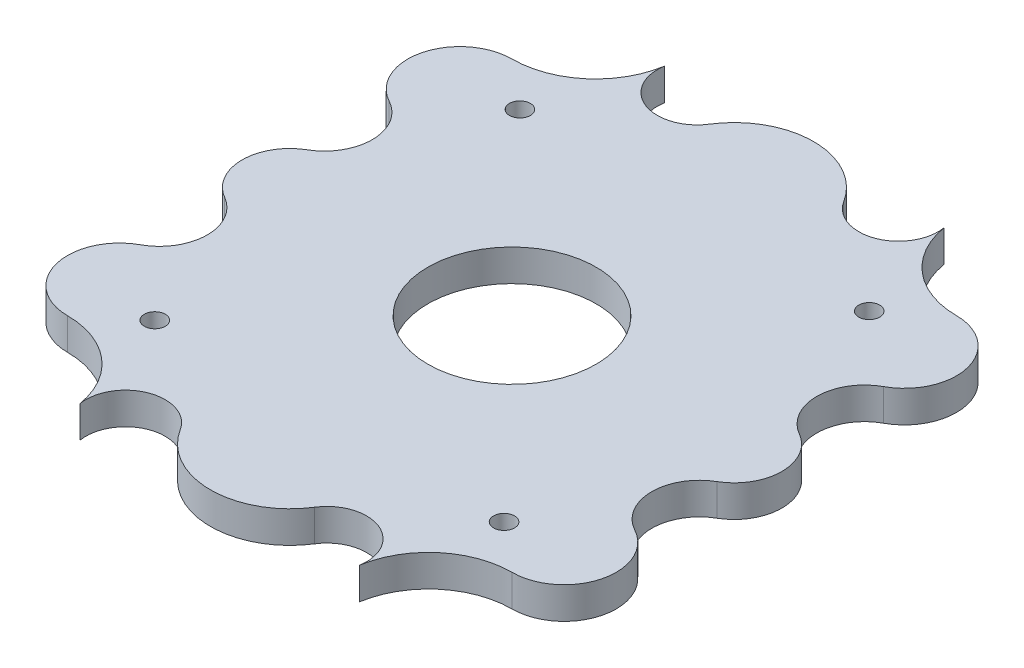
SolidWorks part; units mm, degrees
ref_plane "Alzado" through (0, 0, 0) normal (0, 0, 1) x (1, 0, 0)
ref_plane "Planta" through (0, 0, 0) normal (0, 1, 0) x (1, 0, 0)
ref_plane "Vista lateral" through (0, 0, 0) normal (1, 0, 0) x (0, 0, -1)
sketch "Croquis1" plane through (0, 0, 0) normal (0, 1, 0) x (1, 0, 0)
  line L0 (0, 138.5041) -> (0, -177.2184) construction
  line L2 (-70, -70) -> (-70, 70)
  line L4 (70, -70) -> (70, 70)
  line L5 (-70, -70) -> (70, 70) construction
  line L6 (-70, 70) -> (70, -70) construction
  line L7 (-103.4324, 0) -> (144.2109, 0) construction
  arc A1 (-21.1476, -83.3333) -> (21.1476, -83.3333) centre (0, -70) ccw
  arc A5 (-21.1476, -83.3333) -> (-44.0559, -92.0276) centre (-31.7214, -90) ccw
  arc A6 (-44.0559, -92.0276) -> (-70, -70) centre (-70, -96.2923) ccw
  arc A7 (21.1476, -83.3333) -> (44.0559, -92.0276) centre (31.7214, -90) cw
  arc A8 (44.0559, -92.0276) -> (70, -70) centre (70, -96.2923) cw
  arc A9 (44.0559, 92.0276) -> (70, 70) centre (70, 96.2923) ccw
  arc A10 (21.1476, 83.3333) -> (44.0559, 92.0276) centre (31.7214, 90) ccw
  arc A11 (-21.1476, 83.3333) -> (21.1476, 83.3333) centre (0, 70) cw
  arc A12 (-21.1476, 83.3333) -> (-44.0559, 92.0276) centre (-31.7214, 90) cw
  arc A13 (-44.0559, 92.0276) -> (-70, 70) centre (-70, 96.2923) cw
  point P0 (0, 0)
  point P14 (-25, -70)
  point P16 (-70, -70)
  dimension "D4" = 50
  dimension "D6" = 25
  dimension "D1" = 140
  dimension "D2" = 140
extrude "Saliente-Extruir1" add sketch "Croquis1" along normal blind 10
sketch "Croquis2" plane through (0, 10, 0) normal (0, 1, 0) x (1, 0, 0)
  line L0 (70, -70) -> (70, 70) construction
  line L1 (70, 70) -> (70, -70)
  line L2 (0, 152.4123) -> (0, -148.5895) construction
  line L3 (-96.3545, 0) -> (168.0513, 0) construction
  line L4 (-70, 70) -> (-70, -70)
  arc A0 (77.5, -12.9904) -> (77.5, 12.9904) centre (70, 0) ccw
  arc A1 (77.838, 39.1605) -> (77.5, 12.9904) centre (85, 25.9808) ccw
  arc A2 (77.838, 39.1605) -> (70, 70) centre (70, 53.5842) ccw
  arc A3 (77.838, -39.1605) -> (77.5, -12.9904) centre (85, -25.9808) cw
  arc A4 (77.838, -39.1605) -> (70, -70) centre (70, -53.5842) cw
  arc A5 (-77.838, -39.1605) -> (-70, -70) centre (-70, -53.5842) ccw
  arc A6 (-77.838, -39.1605) -> (-77.5, -12.9904) centre (-85, -25.9808) ccw
  arc A7 (-77.5, -12.9904) -> (-77.5, 12.9904) centre (-70, 0) cw
  arc A8 (-77.838, 39.1605) -> (-77.5, 12.9904) centre (-85, 25.9808) cw
  arc A9 (-77.838, 39.1605) -> (-70, 70) centre (-70, 53.5842) cw
  line M11 (-70, 70) -> (-70, -70)
  line M17 (70, -70) -> (70, 70)
  dimension "D1" = 30
  dimension "D2" = 30
extrude "Saliente-Extruir2" add sketch "Croquis2" against normal blind 10 contours A9 A8 M11 | A1 A2 L1 | L1 A3 A0 A1 | L4 A8 A7 A6 | A6 A5 L4 | A4 A3 M17
sketch "Croquis3" plane through (0, 10, 0) normal (0, 1, 0) x (1, 0, 0)
  circle A0 centre (0, 0) radius 26.5
  dimension "D1" = 53
extrude "Cortar-Extruir1" cut sketch "Croquis3" against normal blind 10
hole_wizard "Refrentado para tornillo con cabeza hueca de M61" positions "Croquis3D1" profile "Croquis4" counterbore size "M6" standard "DIN" end condition through all
sketch3d "Croquis3D1"
  line L1 (55, 0, -57.5) -> (55, 0, 57.5) construction
  line L2 (55, 0, -57.5) -> (-55, 0, -57.5) construction
  line L3 (-55, 0, -57.5) -> (-55, 0, 57.5) construction
  line L4 (55, 0, 57.5) -> (-55, 0, 57.5) construction
  line L5 (55, 0, -57.5) -> (-55, 0, 57.5) construction
  line L6 (-55, 0, -57.5) -> (55, 0, 57.5) construction
  point P0 (-55, 0, 57.5)
  point P2 (55, 0, 57.5)
  point P4 (55, 0, -57.5)
  point P6 (-55, 0, -57.5)
  point P9 (0, 0, 0)
  dimension "D1" = 115
  dimension "D2" = 110
sketch "Croquis4" plane through (-55, 0, 57.5) normal (1, 0, 0) x (0, 0, -1)
  line L0 (0, 0) -> (0, 10)
  line L1 (0, 10) -> (3.3, 10)
  line L3 (3.3, 10) -> (3.3, 4.4)
  line L4 (3.3, 4.4) -> (5.5, 4.4)
  line L5 (5.5, 4.4) -> (5.5, 0)
  line L7 (5.5, 0) -> (0, 0)
  line L11 (0, -6.35) -> (0, 107.95) construction
  dimension "Diámetro de taladro hasta el siguiente" = 6.6
  dimension "Profundidad de taladro hasta el siguiente" = 10
  dimension "Diámetro de refrentado" = 11
  dimension "Profundidad de refrentado" = 4.4
